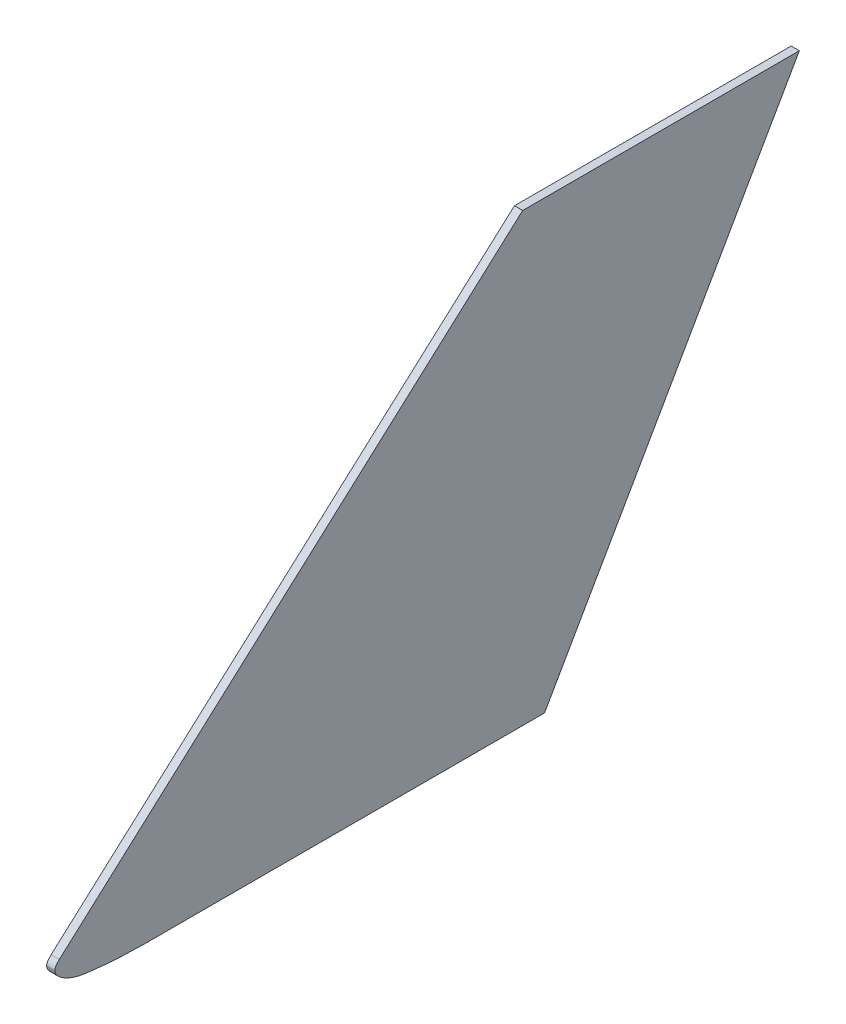
SolidWorks part; units mm, degrees
ref_plane "Front Plane" through (0, 0, 0) normal (0, 0, 1) x (1, 0, 0)
ref_plane "Top Plane" through (0, 0, 0) normal (0, 1, 0) x (1, 0, 0)
ref_plane "Right Plane" through (0, 0, 0) normal (1, 0, 0) x (0, 0, -1)
sketch "Sketch1" plane through (0, 0, 0) normal (1, 0, 0) x (0, 0, -1)
  line L0 (0, 0) -> (168.275, 0)
  line L1 (168.275, 0) -> (251.079, 145)
  line L2 (251.079, 145) -> (161.163, 145)
  line L3 (161.163, 145) -> (0, 0)
  dimension "D1" = 168.275
  dimension "D2" = 145
  dimension "D3" = 82.804
  dimension "D4" = 89.916
extrude "Boss-Extrude1" add sketch "Sketch1" along normal blind 2.667
sketch "Sketch2" plane through (0, 0, 0) normal (-1, 0, 0) x (0, 0, 1)
  line L0 (-58.3067, 0.4912) -> (-40.9692, 0) construction
  line L1 (-131.2701, 15.9151) -> (-125.292, 4.987) construction
  line L2 (-125.292, 4.987) -> (-96.5991, 2.5788) construction
  line L3 (-96.5991, 2.5788) -> (-58.3067, 0.4912) construction
  line L4 (-58.3067, 0.4912) -> (-40.9692, 0) construction
  line L5 (-131.2701, 15.9151) -> (-125.292, 4.987) construction
  line L6 (-125.292, 4.987) -> (-96.5991, 2.5788) construction
  line L7 (-96.5991, 2.5788) -> (-58.3067, 0.4912) construction
  line L8 (-38.2685, 0) -> (1.6038, -0.1367)
  line L10 (-10.613, 9.4828) -> (-7.657, 9.4828)
  line L11 (-7.657, 9.4828) -> (1.6038, -0.1367)
  line L12 (1.6038, -0.1367) -> (1.6562, -0.0616)
  parabola Q0 (-38.2685, 0) -> (-20.4792, 1.1041) focus (-33.037, 71.6752) apex (-27.8636, 0.3753) construction
  parabola Q1 (-38.2685, 0) -> (-20.4792, 1.1041) focus (-33.037, 71.6752) apex (-27.8636, 0.3753)
  spline S0 degree 3 poles (2947.4765, -434.3435) (-73.4571, 47.0874) (5.3401, -77.8318) (37.3208, 136.5775) (-2863.4158, -910.5095) knots -0.404526 -0.404526 -0.404526 -0.404526 0.031804 0.647576 0.647576 0.647576 0.647576 only from (-20.4792, 1.1041) to (-9.0961, 6.9651) construction
  spline S2 degree 3 poles (-20.4792, 1.1041) (-19.7842, 1.1909) (-14.2944, 1.6921) (-9.1863, 4.9601) (-9.0961, 6.9651) knots 0 0 0 0 0.031804 0.095003 0.095003 0.095003 0.095003
  spline S3 degree 3 poles (-3007.8046, 48.534) (86.7182, -53.9587) (-0.8607, 12.5217) (-41.7081, 18.8012) (-289.6607, 26.8358) (-387.7551, -104.9376) (-2759.3658, -1429.6415) knots -0.467092 -0.467092 -0.467092 -0.467092 0.16879 0.324837 0.583849 5.286023 5.286023 5.286023 5.286023 only from (-9.0961, 6.9651) to (-131.2701, 15.9151) construction
  spline S4 degree 3 poles (-9.0961, 6.9651) (-9.0567, 7.842) (-9.65, 8.6866) (-10.613, 9.4828) knots 0.095003 0.095003 0.095003 0.095003 0.122644 0.122644 0.122644 0.122644
extrude "Cut-Extrude1" cut sketch "Sketch2" against normal through all
